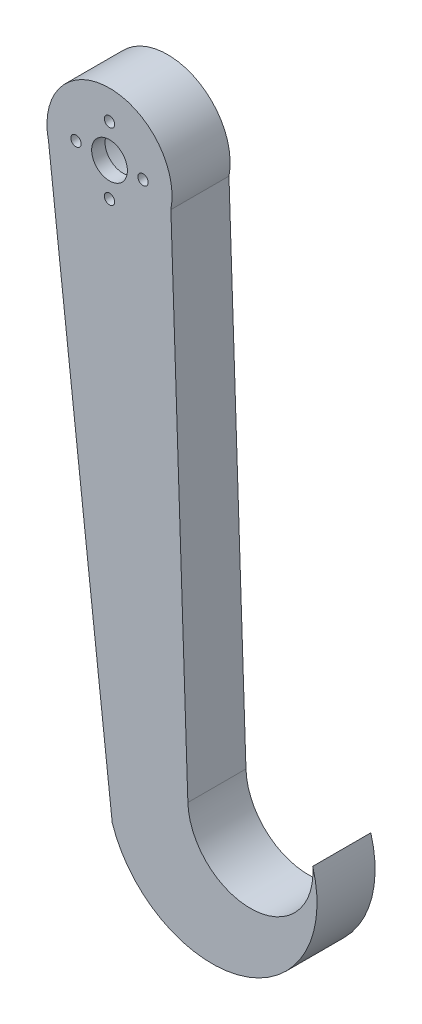
SolidWorks part; units mm, degrees
ref_plane "정면" through (0, 0, 0) normal (0, 0, 1) x (1, 0, 0)
ref_plane "윗면" through (0, 0, 0) normal (0, 1, 0) x (1, 0, 0)
ref_plane "우측면" through (0, 0, 0) normal (1, 0, 0) x (0, 0, -1)
sketch "스케치1" plane through (0, 0, 0) normal (0, 0, 1) x (1, 0, 0)
  circle A0 centre (0, 0) radius 14
  dimension "D1" = 28
extrude "보스-돌출1" add sketch "스케치1" along normal blind 13
sketch "스케치2" plane through (0, 0, 0) normal (0, 0, -1) x (-1, 0, 0)
  circle A0 centre (0, 0) radius 10.6
  dimension "D1" = 21.2
extrude "컷-돌출1" cut sketch "스케치2" against normal blind 10
sketch "스케치3" plane through (0, 0, 13) normal (0, 0, 1) x (1, 0, 0)
  circle A0 centre (0, 0) radius 4
  dimension "D1" = 8
extrude "컷-돌출2" cut sketch "스케치3" against normal blind 10
sketch "스케치6" plane through (0, 0, 13) normal (0, 0, 1) x (1, 0, 0)
  line L0 (0, 0) -> (0, 18.4707) construction
  line L1 (-14, 37.9731) -> (-14, -35.8302) construction
  line L2 (14, 37.9731) -> (14, -35.8302) construction
  line L3 (13.7356, -2.7081) -> (17.5397, -115.7081)
  line L4 (-13.649, -3.1153) -> (0.6086, -128.1153)
  arc A0 (17.5397, -115.7081) -> (45.486, -114.1067) centre (31.5317, -115.2371) ccw
  circle A1 centre (0, 0) radius 14 construction
  arc A2 (0.6086, -128.1153) -> (45.486, -114.1067) centre (22.9334, -120.746) ccw
  arc A3 (-13.649, -3.1153) -> (13.7356, -2.7081) centre (0, 0) ccw
  dimension "D3" = 14
  dimension "D1" = 113
  dimension "D2" = 125
extrude "보스-돌출3" add sketch "스케치6" against normal blind 13
sketch "스케치7" plane through (0, 0, 10) normal (0, 0, -1) x (-1, 0, 0)
  line L1 (9.1626, 0) -> (-10.2595, 0) construction
  circle A0 centre (7.5, 0) radius 1.15
  circle A1 centre (0, -7.5) radius 1.15
  circle A2 centre (-7.5, 0) radius 1.15
  circle A3 centre (0, 7.5) radius 1.15
  point P14 (0, 0)
  dimension "D1" = 2.3
  dimension "D2" = 7.5
  dimension "D3" = 4
extrude "컷-돌출3" cut sketch "스케치7" against normal blind 14
